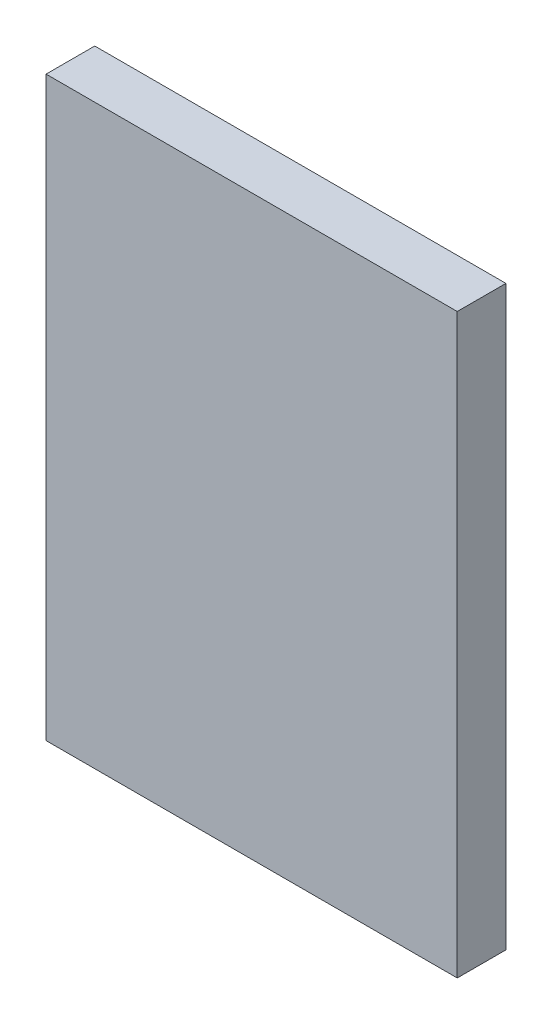
SolidWorks part; units mm, degrees
ref_plane "Front Plane" through (0, 0, 0) normal (0, 0, 1) x (1, 0, 0)
ref_plane "Top Plane" through (0, 0, 0) normal (0, 1, 0) x (1, 0, 0)
ref_plane "Right Plane" through (0, 0, 0) normal (1, 0, 0) x (0, 0, -1)
sketch "Sketch1" plane through (0, 0, 0) normal (0, 0, 1) x (1, 0, 0)
  line L1 (26.8224, -37.6555) -> (-26.8224, -37.6555)
  line L2 (26.8224, -37.6555) -> (26.8224, 37.6555)
  line L3 (26.8224, 37.6555) -> (-26.8224, 37.6555)
  line L4 (-26.8224, -37.6555) -> (-26.8224, 37.6555)
  line L5 (26.8224, -37.6555) -> (-26.8224, 37.6555) construction
  line L6 (26.8224, 37.6555) -> (-26.8224, -37.6555) construction
  point P0 (0, 0)
  dimension "D1" = 53.6448
  dimension "D2" = 75.311
extrude "Boss-Extrude1" add sketch "Sketch1" along normal blind 6.35
